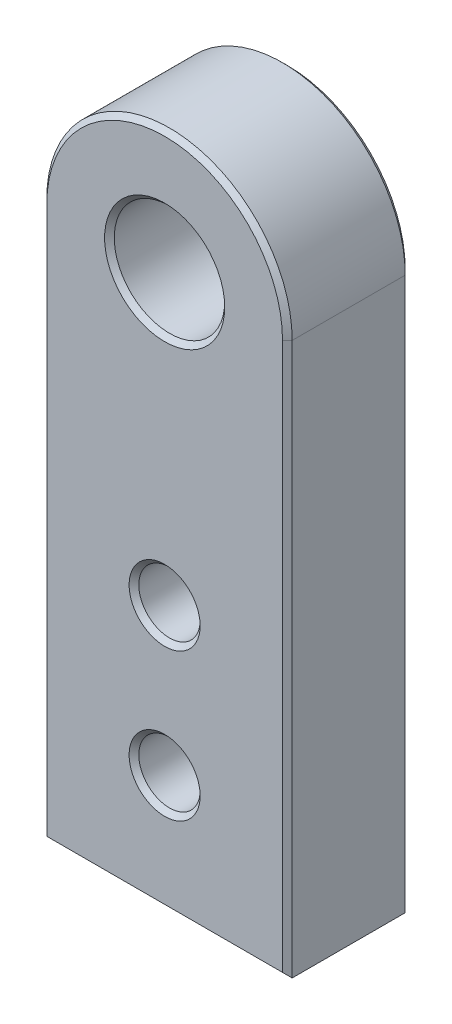
SolidWorks part; units mm, degrees
ref_plane "Front Plane" through (0, 0, 0) normal (0, 0, 1) x (1, 0, 0)
ref_plane "Top Plane" through (0, 0, 0) normal (0, 1, 0) x (1, 0, 0)
ref_plane "Right Plane" through (0, 0, 0) normal (1, 0, 0) x (0, 0, -1)
sketch "Sketch1" plane through (0, 0, 0) normal (0, 0, 1) x (1, 0, 0)
  line L0 (25.4, 40.64) -> (0, 40.64) construction
  line L1 (0, 0) -> (25.4, 0)
  line L2 (0, 0) -> (0, 40.64)
  line L4 (25.4, 0) -> (25.4, 40.64)
  line L5 (0, 57.15) -> (0, 40.64)
  line L6 (12.7, 57.15) -> (12.7, 0) construction
  line L7 (25.4, 57.15) -> (25.4, 40.64)
  arc A3 (25.4, 57.15) -> (0, 57.15) centre (12.7, 57.15) ccw
  circle A4 centre (12.7, 57.15) radius 5.715
  circle A5 centre (12.7, 27.305) radius 3.175
  circle A6 centre (12.7, 12.065) radius 3.175
  point P6 (12.7, 40.64)
  dimension "D1" = 57.15
  dimension "D2" = 12.7
  dimension "D7" = 6.35
  dimension "D8" = 11.43
  dimension "D3" = 40.64
  dimension "D4" = 25.4
  dimension "D5" = 15.24
  dimension "D6" = 29.845
extrude "Boss-Extrude1" add sketch "Sketch1" along normal blind 12.7
chamfer "Chamfer1" distance 0.5 angle 45 14 edges at (15.875, 12.065, 0) (18.415, 57.15, 0) (15.875, 27.305, 0) (25.4, 28.575, 0) (12.7, 69.85, 0) (0, 28.575, 0) (12.7, 0, 0) (15.875, 12.065, 12.7) (15.875, 27.305, 12.7) (12.7, 69.85, 12.7) (25.4, 28.575, 12.7) (12.7, 0, 12.7) (0, 28.575, 12.7) (18.415, 57.15, 12.7)
